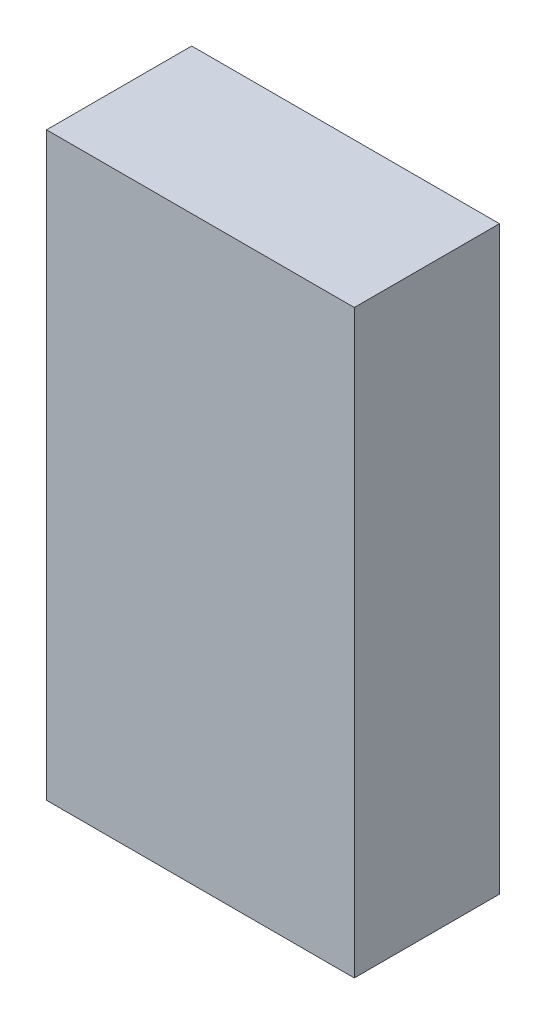
SolidWorks part; units mm, degrees
ref_plane "前基準面" through (0, 0, 0) normal (0, 0, 1) x (1, 0, 0)
ref_plane "上基準面" through (0, 0, 0) normal (0, 1, 0) x (1, 0, 0)
ref_plane "右基準面" through (0, 0, 0) normal (1, 0, 0) x (0, 0, -1)
sketch "草圖1" plane through (0, 0, 0) normal (0, 1, 0) x (1, 0, 0)
  line L1 (-53, 22.5) -> (53, 22.5)
  line L2 (-53, 22.5) -> (-53, -22.5)
  line L3 (-53, -22.5) -> (53, -22.5)
  line L4 (53, 22.5) -> (53, -22.5)
  line L5 (-53, 22.5) -> (53, -22.5) construction
  line L6 (-53, -22.5) -> (53, 22.5) construction
  point P0 (0, 0)
  dimension "D1" = 106
  dimension "D2" = 45
extrude "填料-伸長1" add sketch "草圖1" along normal blind 200
sketch "草圖2" plane through (0, 0, 22.5) normal (0, 0, 1) x (1, 0, 0)
  line L0 (-53, 200) -> (-53, 0) construction
  line L1 (-43, 190) -> (43, 190)
  line L2 (-43, 190) -> (-43, 10)
  line L3 (-43, 10) -> (43, 10)
  line L4 (43, 190) -> (43, 10)
  line L5 (-53, 200) -> (53, 200) construction
  line L6 (53, 200) -> (53, 0) construction
  line L7 (-53, 0) -> (53, 0) construction
  dimension "D1" = 10
  dimension "D2" = 10
  dimension "D3" = 10
  dimension "D4" = 10
extrude "除料-伸長1" cut sketch "草圖2" against normal blind 35
sketch "草圖3" plane through (0, 0, -12.5) normal (0, 0, 1) x (1, 0, 0)
  line L0 (-1043, 150.302) -> (48957, 150.302) construction
  circle A0 centre (-26.6966, 150.302) radius 7.5
  circle A1 centre (-1.6966, 150.302) radius 7.5
  circle A2 centre (23.3034, 150.302) radius 7.5
  dimension "D1" = 15
  dimension "D2" = 15
  dimension "D3" = 15
  dimension "D4" = 25
  dimension "D5" = 25
extrude "除料-伸長2" cut sketch "草圖3" against normal through all
sketch "草圖4" plane through (0, 0, 0) normal (0, -1, 0) x (1, 0, 0)
  line L0 (-53, -22.5) -> (-53, 22.5) construction
  line L1 (-33, 14.5) -> (-8.9694, 14.5)
  line L2 (-33, 14.5) -> (-33, 7.292)
  line L3 (-33, 7.292) -> (-8.9694, 7.292)
  line L4 (-8.9694, 14.5) -> (-8.9694, 7.292)
  line L5 (-53, 22.5) -> (53, 22.5) construction
  dimension "D1" = 20
  dimension "D2" = 8
extrude "除料-伸長4" cut sketch "草圖4" against normal blind 35
sketch "草圖5" plane through (0, 0, 22.5) normal (0, 0, 1) x (1, 0, 0)
  line L1 (-53, 200) -> (53, 200)
  line L2 (-53, 200) -> (-53, 0)
  line L3 (-53, 0) -> (53, 0)
  line L4 (53, 200) -> (53, 0)
extrude "填料-伸長2" add sketch "草圖5" along normal blind 5
